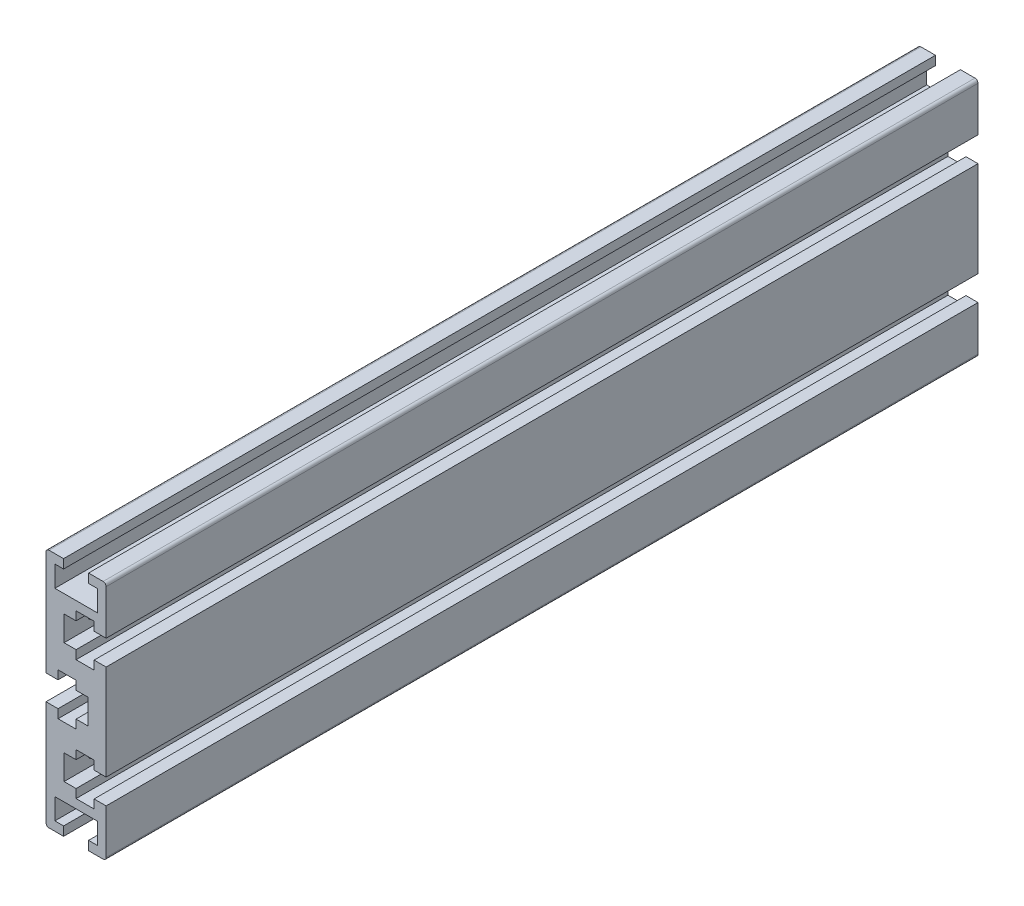
SolidWorks part; units mm, degrees
ref_plane "Plane1" through (0, 0, 0) normal (0, 0, 1) x (1, 0, 0)
ref_plane "Plane2" through (0, 0, 0) normal (0, 1, 0) x (1, 0, 0)
ref_plane "Plane3" through (0, 0, 0) normal (1, 0, 0) x (0, 0, -1)
sketch "Sketch1" plane through (0, 0, 0) normal (0, 0, 1) x (1, 0, 0)
  line L0 (0, 0) -> (75.649, 0) construction
  line L1 (-9, 40) -> (-4.15, 40)
  line L2 (-10, 39) -> (-10, 4.15)
  line L3 (-9, -40) -> (-4.15, -40)
  line L4 (10, 39) -> (10, 24.15)
  line L5 (0, 3.6903) -> (0, 44.6054) construction
  line L6 (-4.15, 40) -> (-4.15, 37)
  line L7 (-4.15, 37) -> (-7.05, 37)
  line L8 (-7.05, 37) -> (-7.05, 30)
  line L9 (-7.05, 30) -> (7.05, 30)
  line L10 (7.05, 30) -> (7.05, 37)
  line L11 (7.05, 37) -> (4.15, 37)
  line L12 (4.15, 37) -> (4.15, 40)
  line L13 (4.15, 40) -> (9, 40)
  line L14 (4.15, -37) -> (4.15, -40)
  line L15 (7.05, -37) -> (4.15, -37)
  line L16 (7.05, -30) -> (7.05, -37)
  line L17 (-7.05, -30) -> (7.05, -30)
  line L18 (-7.05, -37) -> (-7.05, -30)
  line L19 (-4.15, -37) -> (-7.05, -37)
  line L20 (-4.15, -40) -> (-4.15, -37)
  line L21 (4.15, -40) -> (9, -40)
  line L22 (-6, -7.05) -> (0, -7.05)
  line L23 (-10, -4.15) -> (-6, -4.15)
  line L24 (-6, 4.15) -> (-10, 4.15)
  line L25 (0, -7.05) -> (0, -4.15)
  line L26 (-6, -4.15) -> (-6, -7.05)
  line L27 (0, 7.05) -> (-6, 7.05)
  line L28 (-17.4711, 20) -> (26.2798, 20) construction
  line L29 (-6, 7.05) -> (-6, 4.15)
  line L30 (-17.4711, -20) -> (26.2798, -20) construction
  line L31 (-4, -15.85) -> (-4, -24.15)
  line L32 (0, -27.05) -> (0, -24.15)
  line L33 (6, -15.85) -> (10, -15.85)
  line L34 (6, -24.15) -> (6, -27.05)
  line L35 (0, -15.85) -> (0, -12.95)
  line L36 (0, 4.15) -> (4, 4.15)
  line L37 (4, 4.15) -> (4, -4.15)
  line L38 (4, -4.15) -> (0, -4.15)
  line L39 (0, 4.15) -> (0, 7.05)
  line L40 (-10, -4.15) -> (-10, -39)
  line L41 (6, 12.95) -> (6, 15.85)
  line L42 (6, 27.05) -> (0, 27.05)
  line L43 (0, 12.95) -> (6, 12.95)
  line L44 (-4, 24.15) -> (0, 24.15)
  line L45 (10, 24.15) -> (6, 24.15)
  line L46 (0, 15.85) -> (-4, 15.85)
  line L47 (0, 15.85) -> (0, 12.95)
  line L48 (6, 24.15) -> (6, 27.05)
  line L49 (0, -15.85) -> (-4, -15.85)
  line L50 (6, 15.85) -> (10, 15.85)
  line L51 (0, 27.05) -> (0, 24.15)
  line L52 (10, -24.15) -> (6, -24.15)
  line L53 (-4, 15.85) -> (-4, 24.15)
  line L54 (-4, -24.15) -> (0, -24.15)
  line L55 (0, -12.95) -> (6, -12.95)
  line L56 (6, -27.05) -> (0, -27.05)
  line L57 (6, -12.95) -> (6, -15.85)
  line L58 (10, 15.85) -> (10, -15.85)
  line L59 (10, -24.15) -> (10, -39)
  arc A0 (9, -40) -> (10, -39) centre (9, -39) ccw
  arc A1 (-10, -39) -> (-9, -40) centre (-9, -39) ccw
  arc A2 (-9, 40) -> (-10, 39) centre (-9, 39) ccw
  arc A3 (9, 40) -> (10, 39) centre (9, 39) cw
  point P72 (-10, 40)
  point P73 (10, 40)
  point P74 (0, 40)
  point P75 (-10, -40)
  point P76 (10, -40)
  point P77 (0, -40)
  point P78 (10, -20)
  point P79 (-10, 0)
  point P80 (10, 20)
  point P81 (-10, 20)
  point P82 (10, 0)
  point P83 (-10, -20)
extrude "凸台-拉伸1" add sketch "Sketch1" along normal blind 290
hole_wizard "Ø4.5 (4.5) 直径孔1" positions "草图2" profile "草图1" hole size "Ø4.5" standard "Gb" end condition through all
sketch "草图2" plane through (-10, 0, 0) normal (-1, 0, 0) x (0, 0, 1)
  line L0 (290, 40) -> (0, 40) construction
  line L4 (0, 39) -> (0, 4.15) construction
  point P0 (10, 20)
  dimension "D1" = 20
  dimension "D2" = 10
sketch "草图1" plane through (-10, 20, 10) normal (0, 1, 0) x (0, 0, 1)
  line L0 (0, 0) -> (0, 20)
  line L1 (0, 20) -> (2.25, 20)
  line L2 (2.25, 20) -> (2.25, 0)
  line L5 (2.25, 0) -> (0, 0)
  line L11 (0, -6.35) -> (0, 107.95) construction
  dimension "通孔孔直径" = 4.5
  dimension "通孔孔深度" = 20
hole_wizard "Ø4.5 (4.5) 直径孔2" positions "草图4" profile "草图3" hole size "Ø4.5" standard "Gb" end condition through all
sketch "草图4" plane through (-10, 0, 0) normal (-1, 0, 0) x (0, 0, 1)
  line L0 (290, 39) -> (290, 4.15) construction
  line L3 (290, 40) -> (0, 40) construction
  point P0 (280, 20)
  dimension "D1" = 10
  dimension "D2" = 20
sketch "草图3" plane through (-10, 20, 280) normal (0, 1, 0) x (0, 0, 1)
  line L0 (0, 0) -> (0, 20)
  line L1 (0, 20) -> (2.25, 20)
  line L2 (2.25, 20) -> (2.25, 0)
  line L5 (2.25, 0) -> (0, 0)
  line L11 (0, -6.35) -> (0, 107.95) construction
  dimension "通孔孔直径" = 4.5
  dimension "通孔孔深度" = 20
hole_wizard "Ø4.5 (4.5) 直径孔3" positions "草图6" profile "草图5" hole size "Ø4.5" standard "Gb" end condition through all
sketch "草图6" plane through (-10, 0, 0) normal (-1, 0, 0) x (0, 0, 1)
  line L0 (0, -4.15) -> (0, -39) construction
  line L1 (290, -40) -> (0, -40) construction
  point P0 (10, -20)
  dimension "D1" = 10
  dimension "D2" = 20
sketch "草图5" plane through (-10, -20, 10) normal (0, 1, 0) x (0, 0, 1)
  line L0 (0, 0) -> (0, 20)
  line L1 (0, 20) -> (2.25, 20)
  line L2 (2.25, 20) -> (2.25, 0)
  line L5 (2.25, 0) -> (0, 0)
  line L11 (0, -6.35) -> (0, 107.95) construction
  dimension "通孔孔直径" = 4.5
  dimension "通孔孔深度" = 20
hole_wizard "Ø4.5 (4.5) 直径孔4" positions "草图8" profile "草图7" hole size "Ø4.5" standard "Gb" end condition through all
sketch "草图8" plane through (-10, 0, 0) normal (-1, 0, 0) x (0, 0, 1)
  line L0 (290, -4.15) -> (290, -39) construction
  line L1 (290, -40) -> (0, -40) construction
  point P0 (280, -20)
  dimension "D1" = 10
  dimension "D2" = 20
sketch "草图7" plane through (-10, -20, 280) normal (0, 1, 0) x (0, 0, 1)
  line L0 (0, 0) -> (0, 20)
  line L1 (0, 20) -> (2.25, 20)
  line L2 (2.25, 20) -> (2.25, 0)
  line L5 (2.25, 0) -> (0, 0)
  line L11 (0, -6.35) -> (0, 107.95) construction
  dimension "通孔孔直径" = 4.5
  dimension "通孔孔深度" = 20
